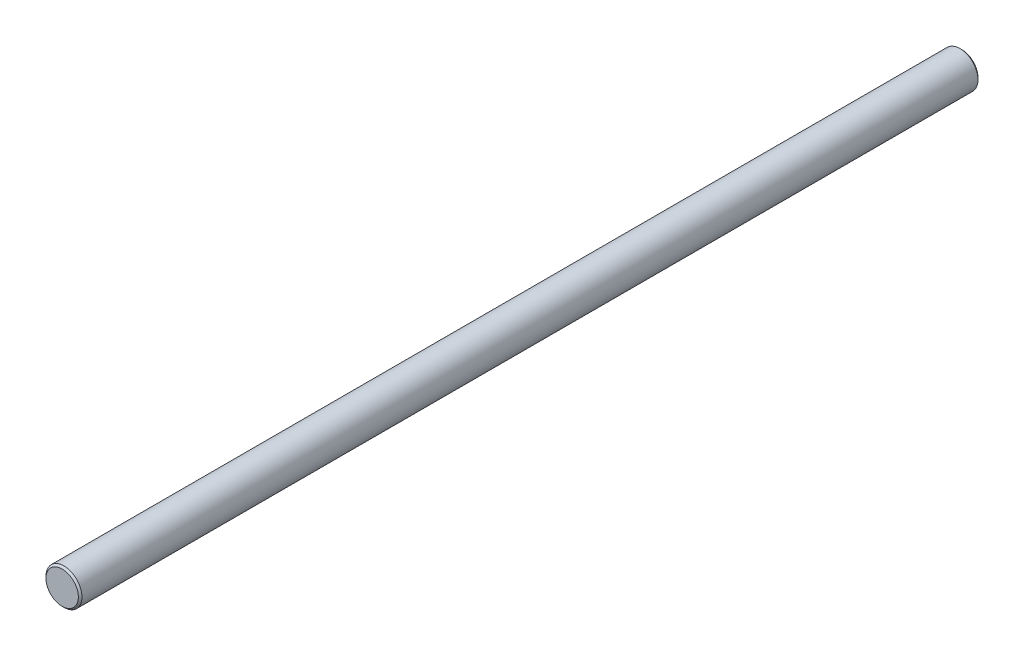
SolidWorks part; units mm, degrees
ref_plane "Front" through (0, 0, 0) normal (0, 0, 1) x (1, 0, 0)
ref_plane "Top" through (0, 0, 0) normal (0, 1, 0) x (1, 0, 0)
ref_plane "Right" through (0, 0, 0) normal (1, 0, 0) x (0, 0, -1)
sketch "Sketch2" plane through (0, 0, 0) normal (0, 0, 1) x (1, 0, 0)
  circle A0 centre (0, 0) radius 10 construction
  dimension "Diameter" = 20
sketch "Sketch3" plane through (0, 0, 0) normal (1, 0, 0) x (0, 0, -1)
  line L0 (-250, 0) -> (250, 0) construction
  point P4 (0, 0)
  dimension "Length" = 500
sketch "Sketch4" plane through (0, 0, 0) normal (0, 0, 1) x (1, 0, 0)
  circle A0 centre (0, 0) radius 10 construction
  circle A1 centre (0, 0) radius 10
extrude "Boss-Extrude1" add sketch "Sketch4" along normal mid plane 500
chamfer "Chamfer1" distance 1 angle 45 2 edges at (10, 0, -250) (10, 0, 250)
equation "\"D1@Boss-Extrude1\"=\"Length@Sketch3\""
equation "\"D1@Chamfer1\"=\"Diameter@Sketch2\"*.05"
